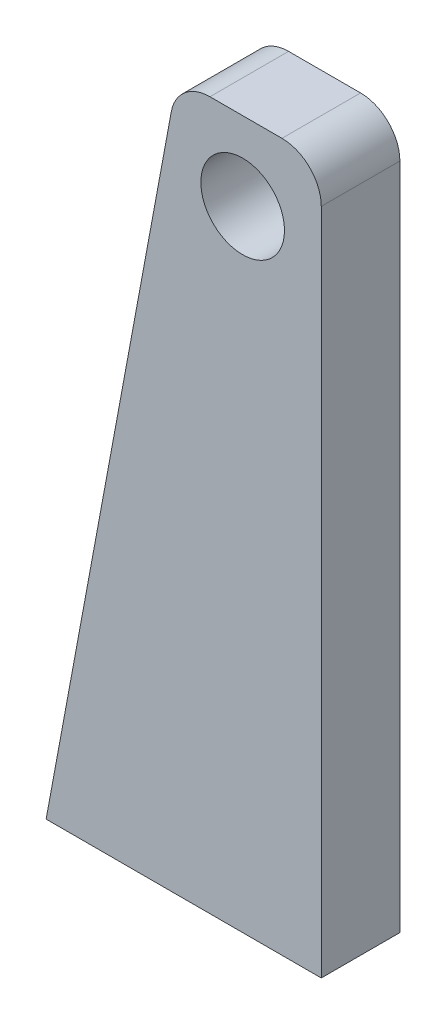
SolidWorks part; units mm, degrees
material "6061 Alloy"
ref_plane "Front Plane" through (0, 0, 0) normal (0, 0, 1) x (1, 0, 0)
ref_plane "Top Plane" through (0, 0, 0) normal (0, 1, 0) x (1, 0, 0)
ref_plane "Right Plane" through (0, 0, 0) normal (1, 0, 0) x (0, 0, -1)
sketch "Sketch1" plane through (0, 0, 0) normal (0, 0, 1) x (1, 0, 0)
  line L0 (0, 0) -> (0, 53.975)
  line L1 (-3.175, 57.15) -> (-8.9905, 57.15)
  line L2 (-12.1124, 54.5537) -> (-22.225, 0)
  line L3 (-22.225, 0) -> (0, 0)
  circle A0 centre (-6.35, 50.8) radius 3.3782
  arc A1 (0, 53.975) -> (-3.175, 57.15) centre (-3.175, 53.975) ccw
  arc A2 (-8.9905, 57.15) -> (-12.1124, 54.5537) centre (-8.9905, 53.975) ccw
  point P13 (0, 57.15)
  dimension "D3" = 6.7564
  dimension "D4" = 6.35
  dimension "D5" = 3.175
  dimension "D1" = 50.8
  dimension "D2" = 22.225
  dimension "D6" = 6.35
  dimension "D7" = 6.35
extrude "Boss-Extrude1" add sketch "Sketch1" along normal blind 6.35
